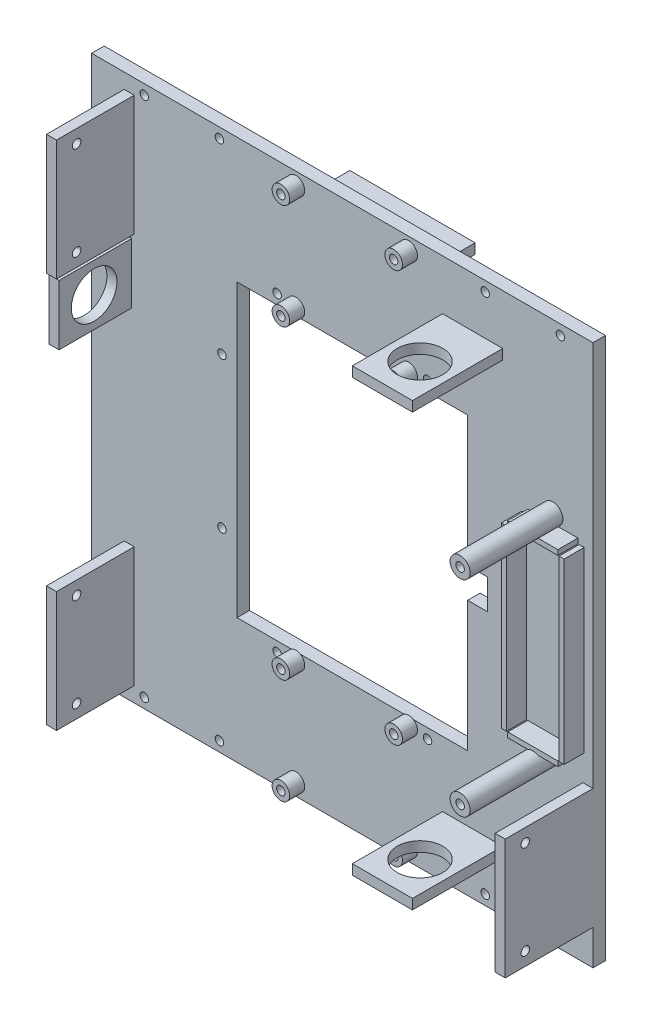
SolidWorks part; units mm, degrees
ref_plane "前视基准面" through (0, 0, 0) normal (0, 0, 1) x (1, 0, 0)
ref_plane "上视基准面" through (0, 0, 0) normal (0, 1, 0) x (1, 0, 0)
ref_plane "右视基准面" through (0, 0, 0) normal (1, 0, 0) x (0, 0, -1)
other "Configuration Table"
sketch "草图1" plane through (0, 0, 0) normal (0, 0, 1) x (1, 0, 0)
  line L1 (-110, -108) -> (110, -108)
  line L2 (-110, -108) -> (-110, 108)
  line L3 (-110, 108) -> (110, 108)
  line L4 (110, -108) -> (110, 108)
  line L5 (-46, -58) -> (46, -58)
  line L6 (-46, -58) -> (-46, 58)
  line L7 (-46, 58) -> (46, 58)
  line L8 (46, -58) -> (46, 58)
extrude "Upper_deck_central_opening_92x116" add sketch "草图1" along normal blind 5 from offset 52
sketch "草图2" plane through (0, 0, 0) normal (0, 0, 1) x (1, 0, 0)
  circle A0 centre (-83, -104) radius 1.7
  circle A1 centre (-83, 104) radius 1.7
  circle A2 centre (-53, -104) radius 1.7
  circle A3 centre (-53, 104) radius 1.7
  circle A4 centre (53, -104) radius 1.7
  circle A5 centre (53, 104) radius 1.7
  circle A6 centre (83, -104) radius 1.7
  circle A7 centre (83, 104) radius 1.7
extrude "Eight_matching_M3_clearance" cut sketch "草图2" against normal blind 7 from offset 58
sketch "草图3" plane through (0, 0, 0) normal (0, 0, 1) x (1, 0, 0)
  circle A0 centre (-56, -30) radius 1.7
  circle A1 centre (-56, 30) radius 1.7
sketch "草图4" plane through (0, 0, 0) normal (0, 0, 1) x (1, 0, 0)
  circle A0 centre (-52, -30) radius 1.7
  circle A1 centre (-52, 30) radius 1.7
extrude "Camera_base_two_M3" cut sketch "草图4" against normal blind 7 from offset 58
sketch "草图5" plane through (0, 0, 0) normal (0, 0, 1) x (1, 0, 0)
  line L1 (96, -110) -> (112, -110)
  line L2 (96, -110) -> (96, 110)
  line L3 (96, 110) -> (112, 110)
  line L4 (112, -110) -> (112, 110)
  line L6 (-112, -110) -> (-104, -110)
  line L7 (-112, -110) -> (-112, 110)
  line L8 (-112, 110) -> (-104, 110)
  line L9 (-104, -110) -> (-104, 110)
extrude "Upper_deck_rear_box_and_pivot_clearance" cut sketch "草图5" against normal blind 7 from offset 58
sketch "草图6" plane through (0, 0, 0) normal (0, 0, 1) x (1, 0, 0)
  line L1 (43, -6) -> (54, -6)
  line L2 (43, -6) -> (43, 6)
  line L3 (43, 6) -> (54, 6)
  line L4 (54, -6) -> (54, 6)
extrude "Battery_clamp_vertical_tool_access" cut sketch "草图6" against normal blind 70 and the other way blind 70
sketch "草图7" plane through (0, 0, 0) normal (0, 0, 1) x (1, 0, 0)
  circle A0 centre (-22.5, -103) radius 3.5
  circle A1 centre (-22.5, -61) radius 3.5
  circle A2 centre (22.5, -103) radius 3.5
  circle A3 centre (22.5, -61) radius 3.5
  circle A4 centre (-22.5, 61) radius 3.5
  circle A5 centre (-22.5, 103) radius 3.5
  circle A6 centre (22.5, 61) radius 3.5
  circle A7 centre (22.5, 103) radius 3.5
extrude "Integral_driver_standoffs_6mm" add sketch "草图7" along normal blind 6 from offset 57
sketch "草图8" plane through (0, 0, 0) normal (0, 0, 1) x (1, 0, 0)
  circle A0 centre (-22.5, -103) radius 1.7
  circle A1 centre (-22.5, -61) radius 1.7
  circle A2 centre (22.5, -103) radius 1.7
  circle A3 centre (22.5, -61) radius 1.7
  circle A4 centre (-22.5, 61) radius 1.7
  circle A5 centre (-22.5, 103) radius 1.7
  circle A6 centre (22.5, 61) radius 1.7
  circle A7 centre (22.5, 103) radius 1.7
  circle A8 centre (-30, -62) radius 1.7
  circle A9 centre (-30, 62) radius 1.7
  circle A10 centre (30, -62) radius 1.7
  circle A11 centre (30, 62) radius 1.7
extrude "Electronics_matching_deck_holes" cut sketch "草图8" against normal blind 13 from offset 64
sketch "草图9" plane through (0, 0, 0) normal (0, 0, 1) x (1, 0, 0)
  line L1 (67.5, -35.5) -> (69.5, -35.5)
  line L2 (67.5, -35.5) -> (67.5, 35.5)
  line L3 (67.5, 35.5) -> (69.5, 35.5)
  line L4 (69.5, -35.5) -> (69.5, 35.5)
  line L6 (90.5, -35.5) -> (92.5, -35.5)
  line L7 (90.5, -35.5) -> (90.5, 35.5)
  line L8 (90.5, 35.5) -> (92.5, 35.5)
  line L9 (92.5, -35.5) -> (92.5, 35.5)
  line L11 (70, -37.5) -> (90, -37.5)
  line L12 (70, -37.5) -> (70, -35.5)
  line L13 (70, -35.5) -> (90, -35.5)
  line L14 (90, -37.5) -> (90, -35.5)
  line L16 (70, 35.5) -> (90, 35.5)
  line L17 (70, 35.5) -> (70, 37.5)
  line L18 (70, 37.5) -> (90, 37.5)
  line L19 (90, 35.5) -> (90, 37.5)
extrude "Control_battery_low_locators" add sketch "草图9" along normal blind 8 from offset 57
sketch "草图10" plane through (0, 0, 0) normal (0, 0, 1) x (1, 0, 0)
  circle A0 centre (80, -41) radius 4
  circle A1 centre (80, 41) radius 4
extrude "Control_battery_integral_clamp_posts" add sketch "草图10" along normal blind 37 from offset 57
sketch "草图11" plane through (0, 0, 0) normal (0, 0, 1) x (1, 0, 0)
  circle A0 centre (80, -41) radius 1.7
  circle A1 centre (80, 41) radius 1.7
extrude "Control_battery_M3_through" cut sketch "草图11" against normal blind 44 from offset 95
sketch "草图12" plane through (0, 0, 0) normal (0, 0, 1) x (1, 0, 0)
  line L1 (-25, 91) -> (25, 91)
  line L2 (-25, 91) -> (-25, 95)
  line L3 (-25, 95) -> (25, 95)
  line L4 (25, 91) -> (25, 95)
  line L6 (-25, -95) -> (25, -95)
  line L7 (-25, -95) -> (-25, -91)
  line L8 (-25, -91) -> (25, -91)
  line L9 (25, -95) -> (25, -91)
extrude "Side_IR_direct_underdeck_mounts" add sketch "草图12" along normal blind 19 from offset 33
sketch "草图13" plane through (0, 0, 0) normal (0, 1, 0) x (1, 0, 0)
  circle A0 centre (-18.7, -44) radius 1.7
  circle A1 centre (18.7, -44) radius 1.7
extrude "Side_IR_37p4_pitch" cut sketch "草图13" against normal blind 110 and the other way blind 110
sketch "草图14" plane through (0, 0, 0) normal (0, 0, 1) x (1, 0, 0)
  line L1 (-91, -102) -> (-87, -102)
  line L2 (-91, -102) -> (-91, -54)
  line L3 (-91, -54) -> (-87, -54)
  line L4 (-87, -102) -> (-87, -54)
  line L6 (-91, 54) -> (-87, 54)
  line L7 (-91, 54) -> (-91, 102)
  line L8 (-91, 102) -> (-87, 102)
  line L9 (-87, 54) -> (-87, 102)
extrude "Front_IR_direct_upper_mounts" add sketch "草图14" along normal blind 31 from offset 57
sketch "草图15" plane through (0, 0, 0) normal (1, 0, 0) x (0, 0, -1)
  circle A0 centre (-80, -96.7) radius 1.7
  circle A1 centre (-80, -59.3) radius 1.7
  circle A2 centre (-80, 59.3) radius 1.7
  circle A3 centre (-80, 96.7) radius 1.7
extrude "Front_IR_M3_mounts" cut sketch "草图15" against normal blind 4 from offset 87
sketch "草图16" plane through (0, 0, 0) normal (0, 0, 1) x (1, 0, 0)
  line L1 (92, -94) -> (96, -94)
  line L2 (92, -94) -> (92, -46)
  line L3 (92, -46) -> (96, -46)
  line L4 (96, -94) -> (96, -46)
extrude "Rear_IR_above_tail_not_on_ramp" add sketch "草图16" along normal blind 35 from offset 57
sketch "草图17" plane through (0, 0, 0) normal (1, 0, 0) x (0, 0, -1)
  circle A0 centre (-84, -88.7) radius 1.7
  circle A1 centre (-84, -51.3) radius 1.7
extrude "Rear_IR_M3_mounts" cut sketch "草图17" against normal blind 4 from offset 96
sketch "草图18" plane through (0, 0, 0) normal (0, 0, 1) x (1, 0, 0)
  line L1 (-92, 28) -> (-88, 28)
  line L2 (-92, 28) -> (-92, 52)
  line L3 (-92, 52) -> (-88, 52)
  line L4 (-88, 28) -> (-88, 52)
extrude "Front_photoeye_short_direct_seat" add sketch "草图18" along normal blind 29 from offset 57
sketch "草图19" plane through (0, 0, 0) normal (1, 0, 0) x (0, 0, -1)
  circle A0 centre (-72, 40) radius 9.1
extrude "Front_M18_clearance" cut sketch "草图19" against normal blind 4 from offset 88
sketch "草图20" plane through (0, 0, 0) normal (0, 0, 1) x (1, 0, 0)
  line L1 (36, 84) -> (60, 84)
  line L2 (36, 84) -> (36, 88)
  line L3 (36, 88) -> (60, 88)
  line L4 (60, 84) -> (60, 88)
  line L6 (36, -88) -> (60, -88)
  line L7 (36, -88) -> (36, -84)
  line L8 (36, -84) -> (60, -84)
  line L9 (60, -88) -> (60, -84)
extrude "Side_photoeye_direct_seats" add sketch "草图20" along normal blind 36 from offset 57
sketch "草图21" plane through (0, 0, 0) normal (0, 1, 0) x (1, 0, 0)
  circle A0 centre (48, -78) radius 9.1
extrude "Side_M18_clearances" cut sketch "草图21" against normal blind 110 and the other way blind 110
